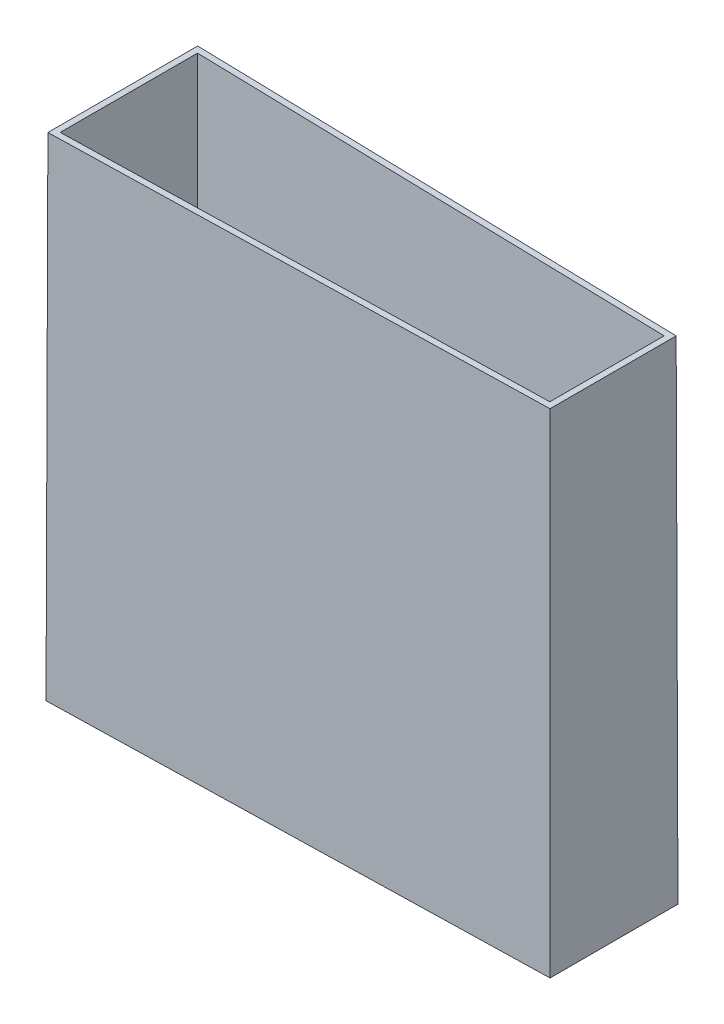
SolidWorks part; units mm, degrees
ref_plane "Front Plane" through (0, 0, 0) normal (0, 0, 1) x (1, 0, 0)
ref_plane "Top Plane" through (0, 0, 0) normal (0, 1, 0) x (1, 0, 0)
ref_plane "Right Plane" through (0, 0, 0) normal (1, 0, 0) x (0, 0, -1)
sketch "Bottom" plane through (0, 0, 0) normal (0, 1, 0) x (1, 0, 0)
  line L8 (-7.6483, 10.6466) -> (-7.6483, -14.2534)
  line L9 (-7.6483, -14.2534) -> (73.1517, -12.2999)
  line L10 (73.1517, -12.2999) -> (73.1517, 8.7001)
  line L11 (73.1517, 8.7001) -> (-7.6483, 10.6466)
  dimension "D1" = 24.9
  dimension "D2" = 21
  dimension "D3" = 80.8
  dimension "D4" = 88.62
ref_plane "Plane1" through (0, 80.8, 0) normal (0, 1, 0) x (1, 0, 0)
sketch "Top" plane through (0, 80.8, 0) normal (0, 1, 0) x (1, 0, 0)
  line L24 (73.0017, -12.1535) -> (73.0017, 8.5537)
  line L25 (-7.4983, -14.0997) -> (73.0017, -12.1535)
  line L26 (-7.4983, 10.4929) -> (-7.4983, -14.0997)
  line L27 (73.0017, 8.5537) -> (-7.4983, 10.4929)
  line L32 (73.0017, -12.1535) -> (73.0017, 8.5537)
  line L33 (-7.4983, -14.0997) -> (73.0017, -12.1535)
  line L34 (-7.4983, 10.4929) -> (-7.4983, -14.0997)
  line L35 (73.0017, 8.5537) -> (-7.4983, 10.4929)
  dimension "D1" = 0.15
loft "Magazine Body" add profiles "Bottom", "Top"
ref_plane "Plane2" through (0, 1, 0) normal (0, -1, 0) x (-1, 0, 0)
sketch "Sketch4" plane through (0, 1, 0) normal (0, -1, 0) x (-1, 0, 0)
  line L9 (6.6483, -13.2289) -> (6.6483, 9.6222)
  line L10 (-72.1517, -11.3238) -> (6.6483, -13.2289)
  line L11 (-72.1517, 7.7239) -> (-72.1517, -11.3238)
  line L12 (6.6483, 9.6222) -> (-72.1517, 7.7239)
  line L13 (6.6483, -13.2289) -> (6.6483, 9.6222)
  line L14 (-72.1517, -11.3238) -> (6.6483, -13.2289)
  line L15 (-72.1517, 7.7239) -> (-72.1517, -11.3238)
  line L16 (6.6483, 9.6222) -> (-72.1517, 7.7239)
  dimension "D1" = 1
sketch "Sketch5" plane through (0, 80.8, 0) normal (0, 1, 0) x (1, 0, 0)
  line L8 (72.0017, -11.1774) -> (72.0017, 7.5775)
  line L9 (72.0017, 7.5775) -> (-6.4983, 9.4686)
  line L10 (-6.4983, 9.4686) -> (-6.4983, -13.0753)
  line L11 (-6.4983, -13.0753) -> (72.0017, -11.1774)
  line L12 (72.0017, -11.1774) -> (72.0017, 7.5775)
  line L13 (72.0017, 7.5775) -> (-6.4983, 9.4686)
  line L14 (-6.4983, 9.4686) -> (-6.4983, -13.0753)
  line L15 (-6.4983, -13.0753) -> (72.0017, -11.1774)
  dimension "D1" = 1
loft "Magazine Inner Cut" cut profiles "Sketch4", "Sketch5"
